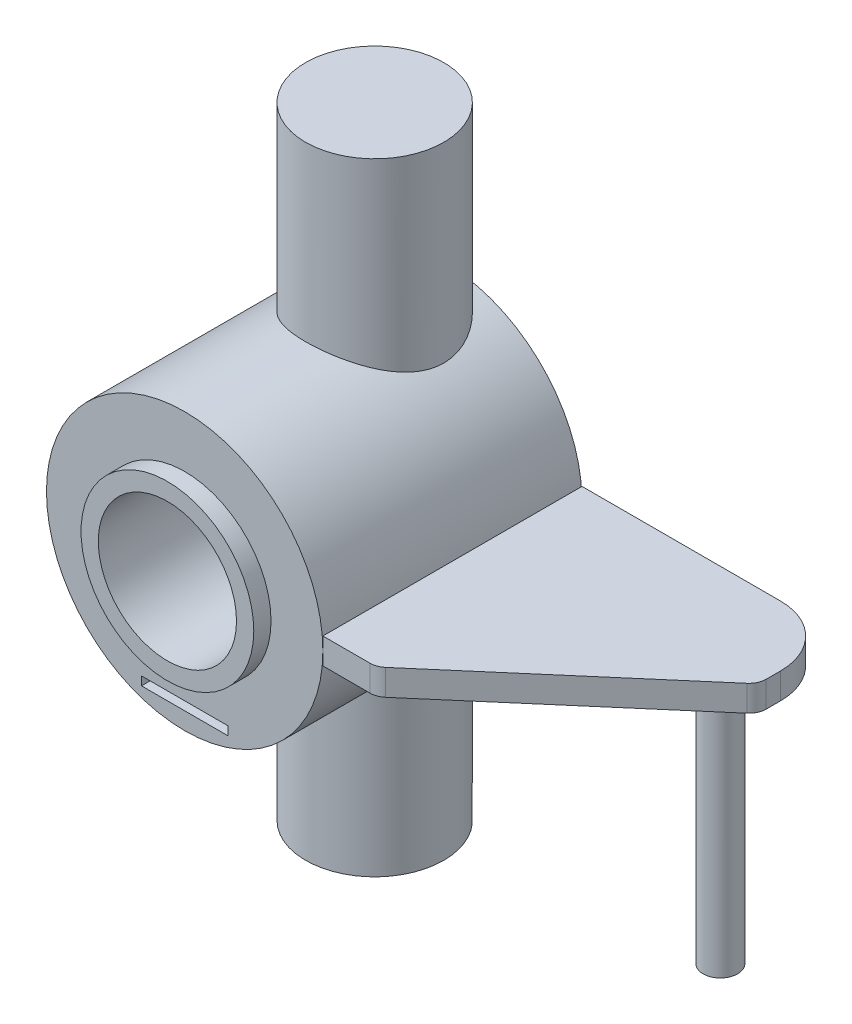
SolidWorks part; units mm, degrees
ref_plane "Front Plane" through (0, 0, 0) normal (0, 0, 1) x (1, 0, 0)
ref_plane "Top Plane" through (0, 0, 0) normal (0, 1, 0) x (1, 0, 0)
ref_plane "Right Plane" through (0, 0, 0) normal (1, 0, 0) x (0, 0, -1)
sketch "Sketch1" plane through (0, 0, 0) normal (0, 0, 1) x (1, 0, 0)
  line L0 (8.8, 8) -> (-8.8, 8) construction
  line L1 (8.8, 0) -> (-8.8, 0) construction
  circle A0 centre (0, 0) radius 8
  dimension "D1" = 16
extrude "Boss-Extrude1" add sketch "Sketch1" along normal blind 15
sketch "Sketch2" plane through (0, 0, 15) normal (0, 0, 1) x (1, 0, 0)
  circle A0 centre (0, 0) radius 5
  circle A1 centre (0, 0) radius 4
  dimension "D1" = 10
  dimension "D2" = 8
extrude "Boss-Extrude2" add sketch "Sketch2" along normal blind 1 contours A0
sketch "Sketch3" plane through (0, 0, 15) normal (0, 0, 1) x (1, 0, 0)
  circle A1 centre (0, 0) radius 4
  circle A2 centre (0, 0) radius 4
  dimension "D1" = 0
extrude "Cut-Extrude1" cut sketch "Sketch3" against normal blind 15
ref_plane "Plane1" through (0, 8, 0) normal (0, 1, 0) x (1, 0, 0)
sketch "Sketch4" plane through (0, 8, 0) normal (0, 1, 0) x (1, 0, 0)
  circle A5 centre (0, -4) radius 4
  dimension "D1" = 8
  dimension "D2" = 4
extrude "Boss-Extrude3" add sketch "Sketch4" along normal blind 10 and the other way up to surface separate body other way up to face at (8, 0, 15)
ref_plane "Plane2" through (0, -8, 0) normal (0, -1, 0) x (-1, 0, 0)
sketch "Sketch6" plane through (0, -8, 0) normal (0, -1, 0) x (-1, 0, 0)
  circle A0 centre (0, -4) radius 4
  dimension "D1" = 4
  dimension "D2" = 8
extrude "Boss-Extrude4" add sketch "Sketch6" along normal blind 10 and the other way up to surface other way up to face at (8, 0, 15)
ref_plane "Plane3" through (8, 0, 0) normal (1, 0, 0) x (0, 0, -1)
sketch "Sketch7" plane through (8, 0, 0) normal (1, 0, 0) x (0, 0, -1)
  line L9 (0, -0.75) -> (-15, -0.75)
  line L10 (0, -0.75) -> (0, 0.75)
  line L11 (0, 0.75) -> (-15, 0.75)
  line L12 (-15, -0.75) -> (-15, 0.75)
  point P4 (0, 0)
  dimension "D1" = 15
  dimension "D2" = 1.5
extrude "Boss-Extrude5" add sketch "Sketch7" along normal blind 15 separate body
sketch "Sketch9" plane through (0, -0.75, 0) normal (0, -1, 0) x (1, 0, 0)
  line L4 (8, 15) -> (8, 0)
  line L5 (8, 0) -> (23, 0)
  line L6 (23, 0) -> (23, 15)
  line L7 (23, 15) -> (8, 15)
  line L8 (8, 15) -> (8, 0)
  line L9 (8, 0) -> (23, 0)
  line L10 (23, 0) -> (23, 15)
  line L11 (23, 15) -> (8, 15)
  circle A0 centre (19.5, 3.5) radius 3.5
  line M8 (23, 0) -> (23, 15)
  dimension "D1" = 0
  dimension "D2" = 7
extrude "Cut-Extrude2" cut sketch "Sketch9" against normal blind 15 contours A0 L9 M8
sketch "Sketch11" plane through (0, -0.75, 0) normal (0, -1, 0) x (-1, 0, 0)
  line L0 (-11.1081, -15) -> (-23, -4.7928) construction
  line L1 (-23, -15) -> (-8, -15) construction
  line L2 (-23, -15) -> (-23, -3.5) construction
  line M3 (-23, -3.5) -> (-23, -15)
  line M4 (-23, -15) -> (-8, -15)
extrude "Cut-Extrude3" cut sketch "Sketch11" against normal blind 15 contours L0 M4 M3
fillet "Fillet1" radius 1 1 edges at (11.1081, 0, 15)
fillet "Fillet2" radius 1 1 edges at (23, 0, 4.7928)
sketch "Sketch12" plane through (0, -0.75, 0) normal (0, -1, 0) x (1, 0, 0)
  arc A2 (19.5, 0) -> (23, 3.5) centre (19.5, 3.5) ccw construction
  arc A3 (19.5, 0) -> (23, 3.5) centre (19.5, 3.5) ccw
  circle A4 centre (19.4463, 3.435) radius 1
  point P1 (21.9749, 1.0251)
  dimension "D1" = 2
  dimension "D3" = 2.5286
  dimension "D2" = 3.435
extrude "Boss-Extrude6" add sketch "Sketch12" along normal blind 15 contours A4
sketch "Sketch13" plane through (0, 0, 15) normal (0, 0, 1) x (1, 0, 0)
  line L0 (2.5, -7) -> (-2.5, -6.5) construction
  line L1 (2.5, -7) -> (-2.5, -7)
  line L2 (2.5, -7) -> (2.5, -6.5)
  line L3 (2.5, -6.5) -> (-2.5, -6.5)
  line L4 (-2.5, -7) -> (-2.5, -6.5)
  point P2 (0, -6.75)
  dimension "D1" = 7
  dimension "D2" = 5
  dimension "D3" = 0.5
extrude "Cut-Extrude4" cut sketch "Sketch13" against normal blind 1
